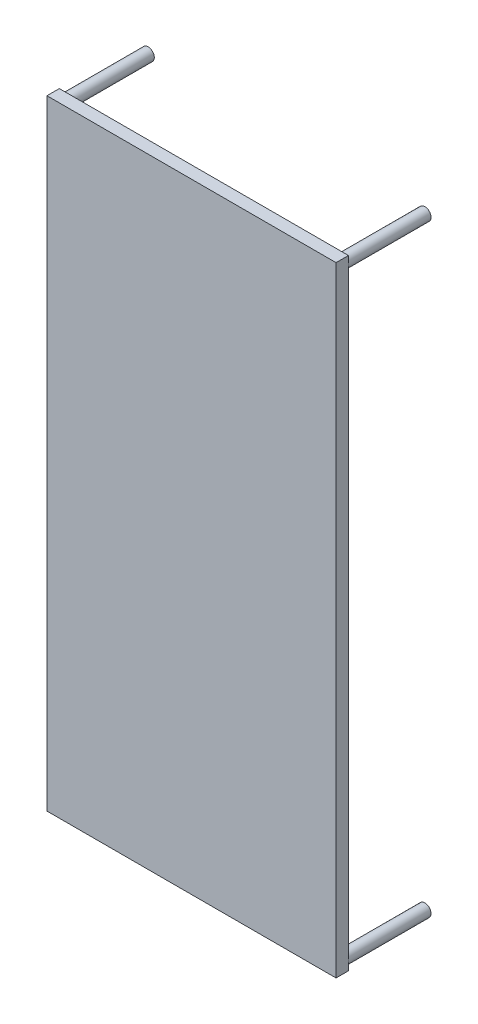
SolidWorks part; units mm, degrees
material "Cedro"
ref_plane "Plano frontal" through (0, 0, 0) normal (0, 0, 1) x (1, 0, 0)
ref_plane "Plano superior" through (0, 0, 0) normal (0, 1, 0) x (1, 0, 0)
ref_plane "Plano direito" through (0, 0, 0) normal (1, 0, 0) x (0, 0, -1)
sketch "Esboço1" plane through (0, 0, 0) normal (0, 0, 1) x (1, 0, 0)
  line L0 (33.5, 150) -> (33.5, 0) construction
  line L1 (-35, 150) -> (35, 150) construction
  line L4 (35, 150) -> (35, 0) construction
  line L5 (33.5, 153.7139) -> (33.5, -14.8623) construction
  line L6 (39.7706, 148) -> (-50.3741, 148) construction
  line L8 (-35, 150) -> (-35, 0) construction
  line L9 (-35, 0) -> (35, 0) construction
  line L10 (-33.5, 166.4047) -> (-33.5, -31.8415) construction
  line L11 (50.334, 2) -> (-96.0704, 2) construction
  circle A0 centre (33.5, 148) radius 1.5
  circle A2 centre (-33.5, 148) radius 1.5
  circle A3 centre (33.5, 2) radius 1.5
  circle A4 centre (-33.5, 2) radius 1.5
  dimension "D1" = 2
  dimension "D3" = 2
  dimension "D5" = 1.5
  dimension "D7" = 2
  dimension "D2" = 1.5
  dimension "D4" = 1.5
  dimension "D6" = 2
extrude "Ressalto-extrusão1" add sketch "Esboço1" along normal blind 20
sketch "Esboço2" plane through (0, 0, 20) normal (0, 0, 1) x (1, 0, 0)
  line L5 (35, 0) -> (-35, 0)
  line L6 (35, 0) -> (35, 150)
  line L7 (35, 150) -> (-35, 150)
  line L8 (-35, 0) -> (-35, 150)
extrude "Ressalto-extrusão2" add sketch "Esboço2" along normal blind 3
